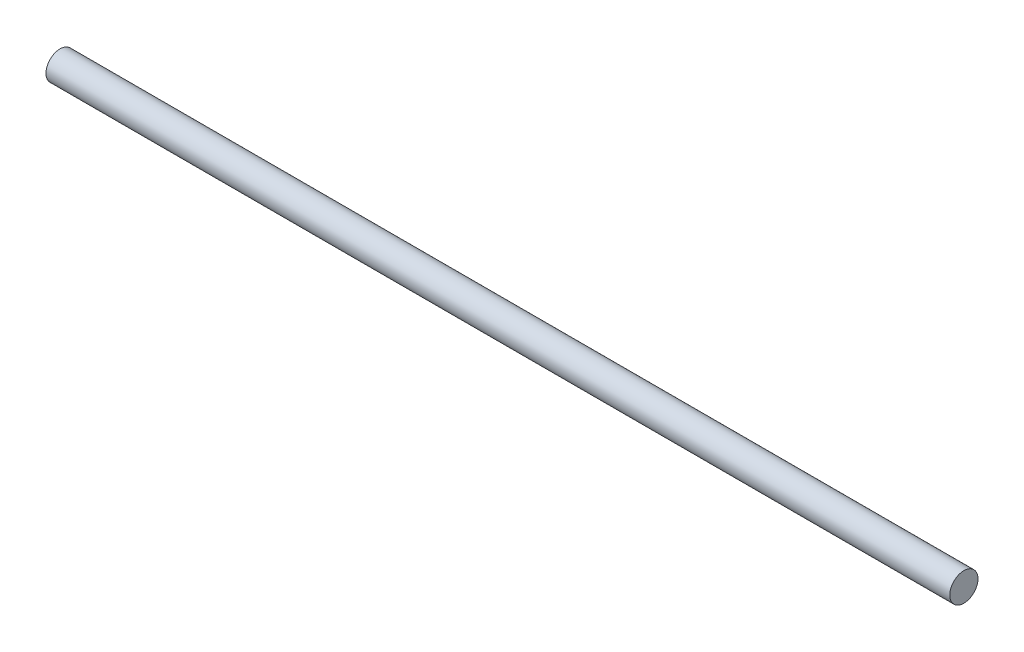
SolidWorks part; units mm, degrees
ref_plane "Front Plane" through (0, 0, 0) normal (0, 0, 1) x (1, 0, 0)
ref_plane "Top Plane" through (0, 0, 0) normal (0, 1, 0) x (1, 0, 0)
ref_plane "Right Plane" through (0, 0, 0) normal (1, 0, 0) x (0, 0, -1)
sketch "Sketch1" plane through (0, 0, 0) normal (1, 0, 0) x (0, 0, -1)
  circle A0 centre (0, 0) radius 1.5875
extrude "Boss-Extrude1" add sketch "Sketch1" along normal mid plane 101.6
